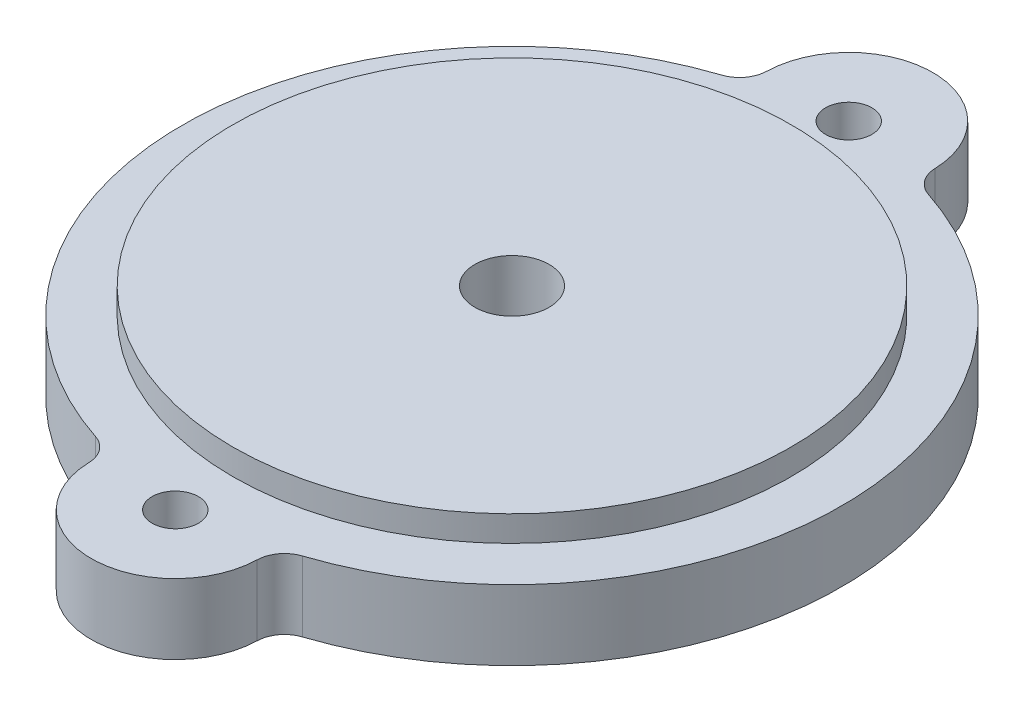
SolidWorks part; units mm, degrees
ref_plane "Front Plane" through (0, 0, 0) normal (0, 0, 1) x (1, 0, 0)
ref_plane "Top Plane" through (0, 0, 0) normal (0, 1, 0) x (1, 0, 0)
ref_plane "Right Plane" through (0, 0, 0) normal (1, 0, 0) x (0, 0, -1)
sketch "Sketch1" plane through (0, 0, 0) normal (0, 1, 0) x (1, 0, 0)
  line L1 (-30, -30) -> (30, -30)
  line L2 (-30, -30) -> (-30, 30)
  line L3 (-30, 30) -> (30, 30)
  line L4 (30, -30) -> (30, 30)
  line L5 (-30, -30) -> (30, 30) construction
  line L6 (-30, 30) -> (30, -30) construction
  circle A0 centre (0, 0) radius 24 construction
  circle A1 centre (0, 24) radius 1.65
  circle A2 centre (0, -24) radius 1.65
  point P0 (0, 0)
  dimension "D2" = 48
  dimension "D3" = 3.3
  dimension "D1" = 60
  dimension "D4" = 2
extrude "Boss-Extrude1" add sketch "Sketch1" along normal blind 5
sketch "Sketch2" plane through (0, 5, 0) normal (0, 1, 0) x (1, 0, 0)
  circle A0 centre (0, 0) radius 19.9
  dimension "D1" = 39.8
extrude "Boss-Extrude2" add sketch "Sketch2" along normal blind 1.83
sketch "Sketch3" plane through (0, 5, 0) normal (0, 1, 0) x (1, 0, 0)
  line L0 (30, 30) -> (-30, 30) construction
  line L1 (-30, -30) -> (30, -30) construction
  arc A0 (5.8695, -22.7552) -> (5.8695, 22.7552) centre (0, 0) ccw
  arc A1 (0, 30) -> (-5.8695, 22.7552) centre (0, 24) ccw
  arc A2 (0, 30) -> (5.8695, 22.7552) centre (0, 24) cw
  arc A3 (0, -30) -> (5.8695, -22.7552) centre (0, -24) ccw
  arc A4 (0, -30) -> (-5.8695, -22.7552) centre (0, -24) cw
  arc A5 (-5.8695, 22.7552) -> (-5.8695, -22.7552) centre (0, 0) ccw
  dimension "D1" = 47
extrude "Cut-Extrude1" cut sketch "Sketch3" against normal through all flip side to cut
sketch "Sketch4" plane through (0, 0, 0) normal (0, -1, 0) x (1, 0, 0)
  circle A0 centre (0, 0) radius 2.65
  dimension "D1" = 5.3
extrude "Cut-Extrude2" cut sketch "Sketch4" against normal through all
fillet "Fillet1" radius 2 4 edges at (5.8695, 2.5, 22.7552) (-5.8695, 2.5, 22.7552) (5.8695, 2.5, -22.7552) (-5.8695, 2.5, -22.7552)
